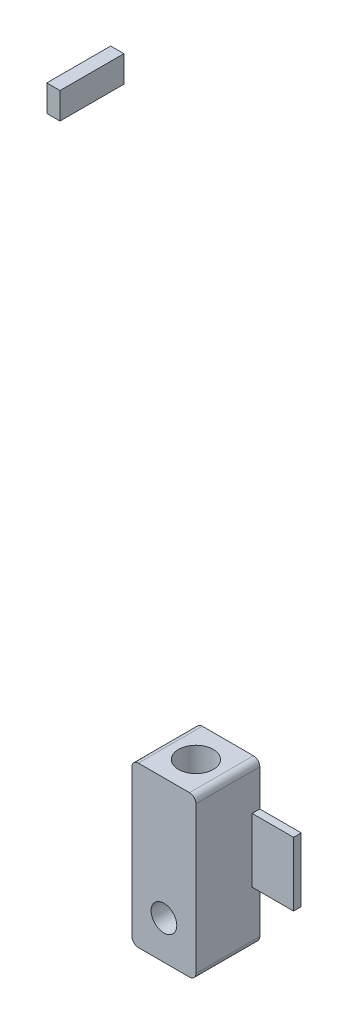
SolidWorks part; units mm, degrees
material "6061-T6 (SS)"
ref_plane "Front Plane" through (0, 0, 0) normal (0, 0, 1) x (1, 0, 0)
ref_plane "Top Plane" through (0, 0, 0) normal (0, 1, 0) x (1, 0, 0)
ref_plane "Right Plane" through (0, 0, 0) normal (1, 0, 0) x (0, 0, -1)
sketch "Sketch1" plane through (0, 0, 0) normal (1, 0, 0) x (0, 0, -1)
  line L0 (-6.35, -3.1496) -> (6.35, -3.1496) construction
  line L1 (-6.35, -15.875) -> (6.35, -15.875)
  line L2 (-6.35, -15.875) -> (-6.35, 15.875)
  line L3 (-6.35, 15.875) -> (6.35, 15.875)
  line L4 (6.35, -15.875) -> (6.35, 15.875)
  line L5 (-6.35, -15.875) -> (6.35, 15.875) construction
  line L6 (-6.35, 15.875) -> (6.35, -15.875) construction
  line L7 (-6.35, -8.255) -> (6.35, -8.255) construction
  line L8 (-6.35, 3.175) -> (6.35, 3.175) construction
  point P0 (0, 0)
  dimension "D1" = 31.75
  dimension "D2" = 12.7
  dimension "D3" = 12.7
  dimension "D4" = 5.1054
  dimension "D5" = 7.62
extrude "Boss-Extrude1" add sketch "Sketch1" along normal mid plane 12.7
sketch "Sketch5" plane through (0, 15.875, 0) normal (0, 1, 0) x (1, 0, 0)
  circle A0 centre (0, 0) radius 2.2221 construction
hole_wizard "5/16-24 Tapped Hole1" positions "Sketch6" profile "Sketch7" tap size "5/16-24" standard "ANSI Inch"
sketch "Sketch6" plane through (0, 15.875, 0) normal (0, 1, 0) x (1, 0, 0)
  point P0 (0, 0)
cosmetic thread "Hole Thread1" parameters "D1"=12.7, "D2"=7.9375
sketch "Sketch7" plane through (0, 15.875, 0) normal (1, 0, 0) x (0, 0, 1)
  line L0 (0, 0) -> (0, 14.7756)
  line L1 (0, 14.7756) -> (3.4544, 12.7)
  line L2 (3.4544, 12.7) -> (3.4544, 0)
  line L5 (3.4544, 0) -> (0, 0)
  line L10 (0, 14.7756) -> (-3.4544, 12.7) construction
  line L11 (0, -6.35) -> (0, 107.95) construction
  dimension "Tap Drill Dia." = 6.9088
  dimension "Tap Drill Depth" = 12.7
  dimension "Drill Angle" = 118
sketch "Sketch8" plane through (0, 0, 6.35) normal (0, 0, 1) x (1, 0, 0)
  line L0 (6.35, -15.875) -> (-6.35, -15.875) construction
  circle A0 centre (0, -8.255) radius 2.5527
  dimension "D1" = 5.1054
  dimension "D2" = 7.62
extrude "Cut-Extrude1" cut sketch "Sketch8" against normal through all both and the other way through all
sketch "Sketch11" plane through (0, -15.875, 0) normal (0, -1, 0) x (1, 0, 0)
  line L0 (6.35, 6.35) -> (-6.35, 6.35) construction
  line L1 (6.35, -6.35) -> (-6.35, -6.35) construction
  line L2 (3.175, 6.35) -> (4.7625, 6.35)
  line L3 (-4.7625, -6.35) -> (-3.175, -6.35)
  line L4 (-3.175, 0) -> (3.175, 0) construction
  arc A0 (3.175, 6.35) -> (4.7625, 6.35) centre (3.9688, 6.35) ccw
  arc A1 (-4.7625, -6.35) -> (-3.175, -6.35) centre (-3.9688, -6.35) cw
  point P8 (0, 0)
  dimension "D1" = 0.7937
  dimension "D2" = 6.35
extrude "Cut-Extrude2" [suppressed] cut sketch "Sketch11" against normal blind 12.7
sketch "Sketch13" plane through (0, 0, -6.35) normal (0, 0, -1) x (-1, 0, 0)
  line L0 (-6.35, 15.875) -> (-6.35, -15.875) construction
  line L1 (23.2833, 123.825) -> (20.6534, 123.825)
  line L2 (23.2833, 123.825) -> (23.2833, 118.5652)
  line L3 (23.2833, 118.5652) -> (20.6534, 118.5652)
  line L4 (20.6534, 123.825) -> (20.6534, 118.5652)
  line L5 (23.2833, 123.825) -> (20.6534, 118.5652) construction
  line L6 (23.2833, 118.5652) -> (20.6534, 123.825) construction
  line L7 (6.35, -15.875) -> (6.35, 15.875) construction
  line L8 (23.2833, 123.825) -> (-52.9167, 123.825) construction
  line L9 (23.2833, 123.825) -> (23.2833, -28.575) construction
  line L10 (23.2833, -28.575) -> (-52.9167, -28.575) construction
  line L11 (-52.9167, 123.825) -> (-52.9167, -28.575) construction
  line L12 (23.2833, 123.825) -> (-52.9167, -28.575) construction
  line L13 (23.2833, -28.575) -> (-52.9167, 123.825) construction
  line L14 (-6.35, -15.875) -> (6.35, -15.875) construction
  point P4 (21.9684, 121.1951)
  point P10 (-14.8167, 47.625)
  dimension "D1" = 76.2
  dimension "D2" = 16.9333
  dimension "D3" = 29.6333
  dimension "D4" = 152.4
  dimension "D5" = 12.7
extrude "Boss-Extrude2" add sketch "Sketch13" against normal up to surface (12.7 mm away) separate body up to face at (-2.5527, -8.255, 6.35)
sketch "Sketch14" plane through (0, 0, -6.35) normal (0, 0, -1) x (-1, 0, 0)
  line L0 (6.35, 7.3483) -> (6.35, -5.3517)
  line L1 (6.35, 7.3483) -> (13.1409, 7.3483)
  line L2 (6.35, -5.3517) -> (13.1409, -5.3517)
  line L3 (13.1409, 7.3483) -> (13.1409, -5.3517)
  line L4 (6.35, -15.875) -> (6.35, 15.875) construction
  line L5 (-6.35, -5.3517) -> (-6.35, 7.3483)
  line L6 (-6.35, -5.3517) -> (-14.5825, -5.3517)
  line L7 (-6.35, 7.3483) -> (-14.5825, 7.3483)
  line L8 (-14.5825, -5.3517) -> (-14.5825, 7.3483)
  line L9 (-6.35, -15.875) -> (-6.35, 15.875) construction
  dimension "D1" = 12.7
extrude "Boss-Extrude3" add sketch "Sketch14" against normal blind 1.524
sketch "Sketch15" [suppressed] plane through (0, 0, 6.35) normal (0, 0, 1) x (1, 0, 0)
  line L0 (3.175, -15.875) -> (4.7625, -15.875)
fillet "Fillet1" radius 1.27 4 edges at (6.35, 15.875, 0) (-6.35, 15.875, 0) (-6.35, -15.875, 0) (6.35, -15.875, 0)
